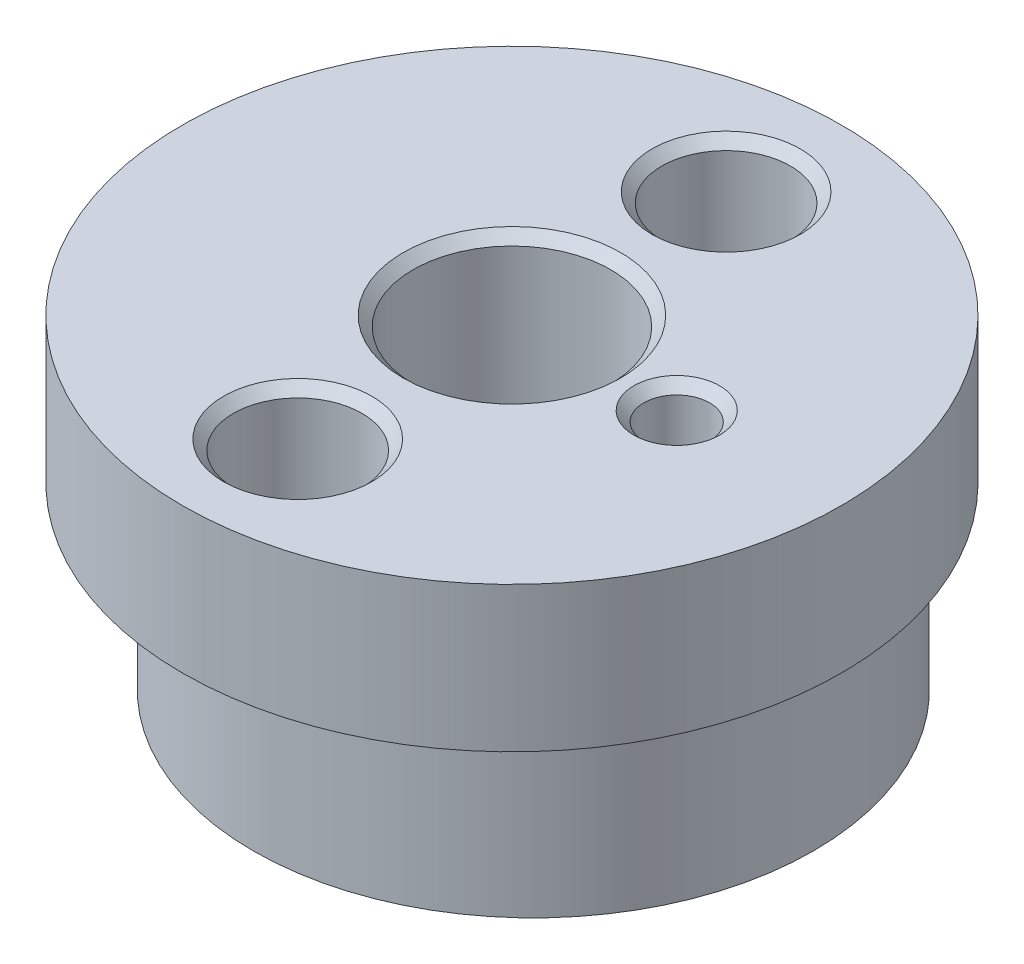
SolidWorks part; units mm, degrees
ref_plane "Front Plane" through (0, 0, 0) normal (0, 0, 1) x (1, 0, 0)
ref_plane "Top Plane" through (0, 0, 0) normal (0, 1, 0) x (1, 0, 0)
ref_plane "Right Plane" through (0, 0, 0) normal (1, 0, 0) x (0, 0, -1)
sketch "Sketch1" plane through (0, 0, 0) normal (0, 1, 0) x (1, 0, 0)
  circle A0 centre (0, 0) radius 8.5
  dimension "D1" = 17
extrude "Boss-Extrude1" add sketch "Sketch1" along normal blind 5.5
sketch "Sketch2" plane through (0, 5.5, 0) normal (0, 1, 0) x (1, 0, 0)
  circle A0 centre (-0.65, 0) radius 10
  dimension "D1" = 20
  dimension "D2" = 0.65
extrude "Boss-Extrude2" add sketch "Sketch2" along normal blind 4 and the other way blind 0.4
sketch "Sketch3" plane through (0, 0, 0) normal (0, -1, 0) x (1, 0, 0)
  circle A0 centre (-0.65, 0) radius 3
  circle A3 centre (-0.65, 0) radius 10 construction
  dimension "D1" = 6
extrude "Cut-Extrude1" cut sketch "Sketch3" against normal through all
sketch "Sketch6" plane through (0, 0, 0) normal (0, -1, 0) x (1, 0, 0)
  line L3 (4.35, 0) -> (0, 0) construction
  circle A0 centre (0, 0) radius 8.5 construction
  circle A2 centre (0, 0) radius 8.5 construction
  circle A4 centre (4.35, 0) radius 1
  dimension "D1" = 2
extrude "Cut-Extrude4" cut sketch "Sketch6" against normal through all contours A4
hole_wizard "Ø3.2 (3.2) Diameter Hole1" positions "Sketch7" profile "Sketch8" hole size "Ø3.2" standard "DIN" end condition up to next
sketch "Sketch7" plane through (0, 0, 0) normal (0, -1, 0) x (-1, 0, 0)
  line L0 (0.65, -6.5) -> (0.65, 0)
  line L1 (0.65, 0) -> (0.65, 6.5)
  circle A0 centre (0.65, 0) radius 6.5
  circle A1 centre (0.65, 0) radius 3 construction
  point P0 (0.65, 6.5)
  point P2 (0.65, -6.5)
  dimension "D1" = 13
sketch "Sketch8" plane through (-0.65, 0, -6.5) normal (1, 0, 0) x (0, 0, -1)
  line L0 (0, 0) -> (0, 9.5)
  line L1 (0, 9.5) -> (1.6, 9.5)
  line L2 (1.6, 9.5) -> (1.6, 0)
  line L5 (1.6, 0) -> (0, 0)
  line L11 (0, -6.35) -> (0, 107.95) construction
  dimension "Thru Hole Dia." = 3.2
  dimension "Thru Hole Depth" = 9.5
sketch "Sketch10" plane through (0, 9.5, 0) normal (0, 1, 0) x (1, 0, 0)
  circle A0 centre (-0.65, 6.5) radius 1.95
  circle A1 centre (-0.65, -6.5) radius 1.95
  dimension "D1" = 3.9
extrude "Cut-Extrude5" cut sketch "Sketch10" against normal blind 4
chamfer "Chamfer1" distance 0.3 angle 45 8 edges at (-0.65, 9.5, -4.55) (-0.65, 9.5, 8.45) (-0.65, 0, 4.9) (-0.65, 0, -8.1) (-0.65, 0, -3) (4.35, 0, -1) (-0.65, 9.5, -3) (4.35, 9.5, -1)
